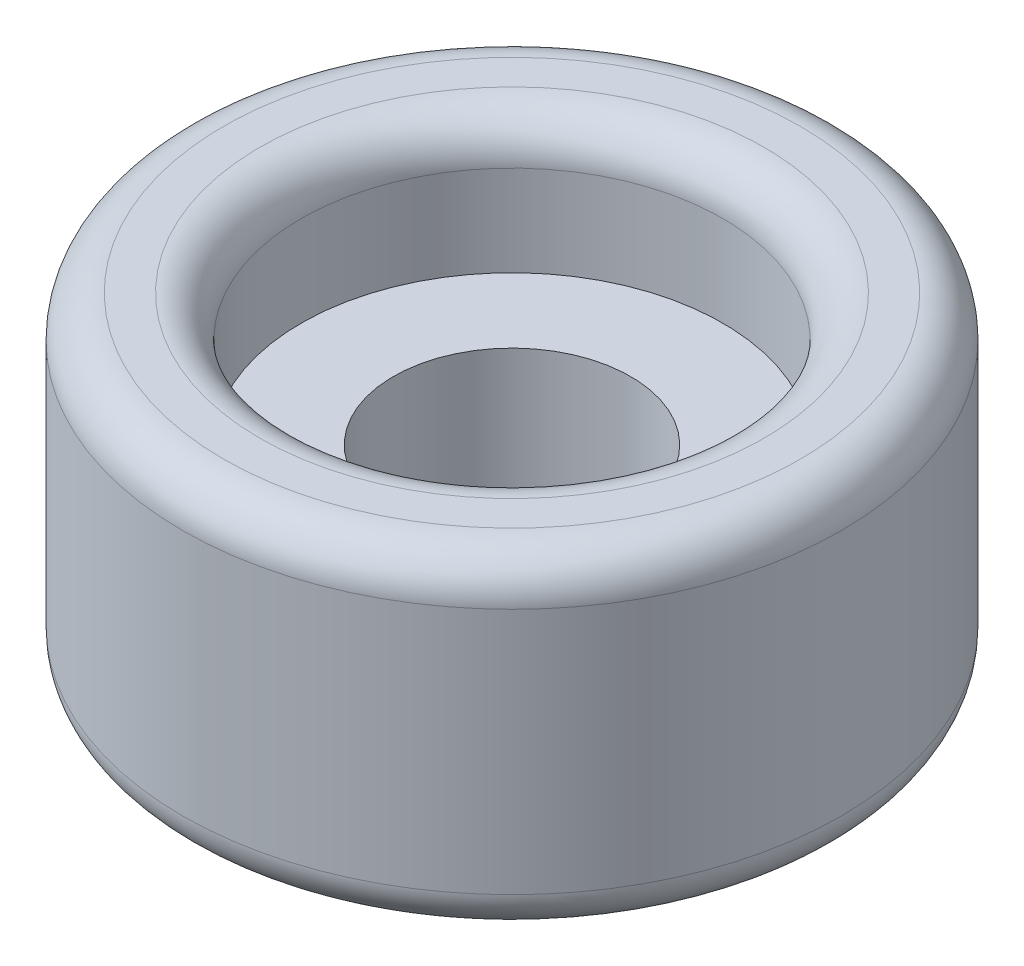
SolidWorks part; units mm, degrees
ref_plane "Front Plane" through (0, 0, 0) normal (0, 0, 1) x (1, 0, 0)
ref_plane "Top Plane" through (0, 0, 0) normal (0, 1, 0) x (1, 0, 0)
ref_plane "Right Plane" through (0, 0, 0) normal (1, 0, 0) x (0, 0, -1)
sketch "Sketch1" plane through (0, 0, 0) normal (0, 1, 0) x (1, 0, 0)
  circle A0 centre (0, 0) radius 6.35
  dimension "D1" = 12.7
extrude "Boss-Extrude1" add sketch "Sketch1" along normal blind 6.35
sketch "Sketch2" plane through (0, 6.35, 0) normal (0, 1, 0) x (1, 0, 0)
  circle A0 centre (0, 0) radius 2.286
  dimension "D1" = 4.572
extrude "Cut-Extrude1" cut sketch "Sketch2" against normal through all
sketch "Sketch3" plane through (0, 6.35, 0) normal (0, 1, 0) x (1, 0, 0)
  circle A0 centre (0, 0) radius 4.064
  dimension "D1" = 8.128
extrude "Cut-Extrude2" cut sketch "Sketch3" against normal blind 2.54
fillet "Fillet1" radius 0.7937 3 edges at (0, 6.35, 6.35) (0, 6.35, 4.064) (0, 0, 6.35)
